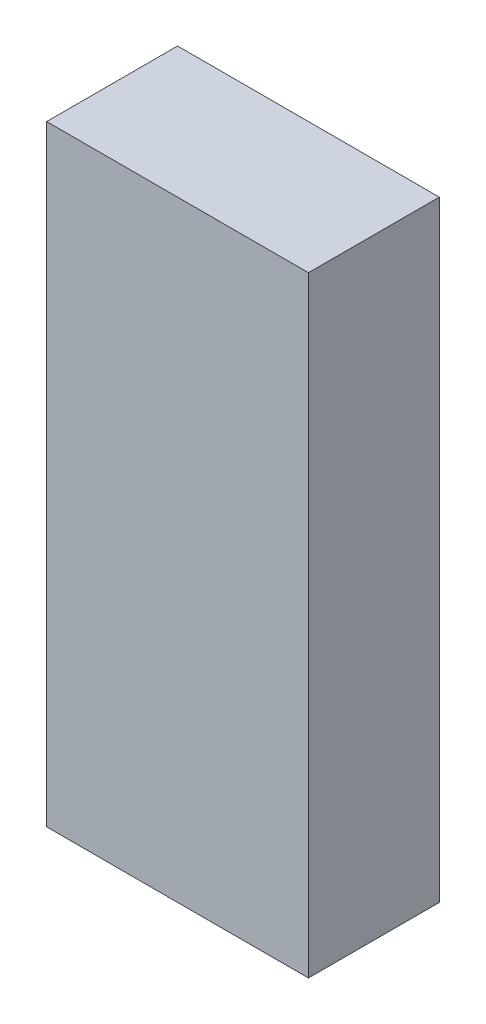
SolidWorks part; units mm, degrees
ref_plane "Front Plane" through (0, 0, 0) normal (0, 0, 1) x (1, 0, 0)
ref_plane "Top Plane" through (0, 0, 0) normal (0, 1, 0) x (1, 0, 0)
ref_plane "Right Plane" through (0, 0, 0) normal (1, 0, 0) x (0, 0, -1)
sketch "Sketch1" plane through (0, 0, 0) normal (0, 1, 0) x (1, 0, 0)
  line L1 (-38.1, -19.05) -> (38.1, -19.05)
  line L2 (-38.1, -19.05) -> (-38.1, 19.05)
  line L3 (-38.1, 19.05) -> (38.1, 19.05)
  line L4 (38.1, -19.05) -> (38.1, 19.05)
  line L5 (-38.1, -19.05) -> (38.1, 19.05) construction
  line L6 (-38.1, 19.05) -> (38.1, -19.05) construction
  point P0 (0, 0)
  dimension "D1" = 76.2
extrude "Boss-Extrude1" add sketch "Sketch1" along normal blind 177.8
